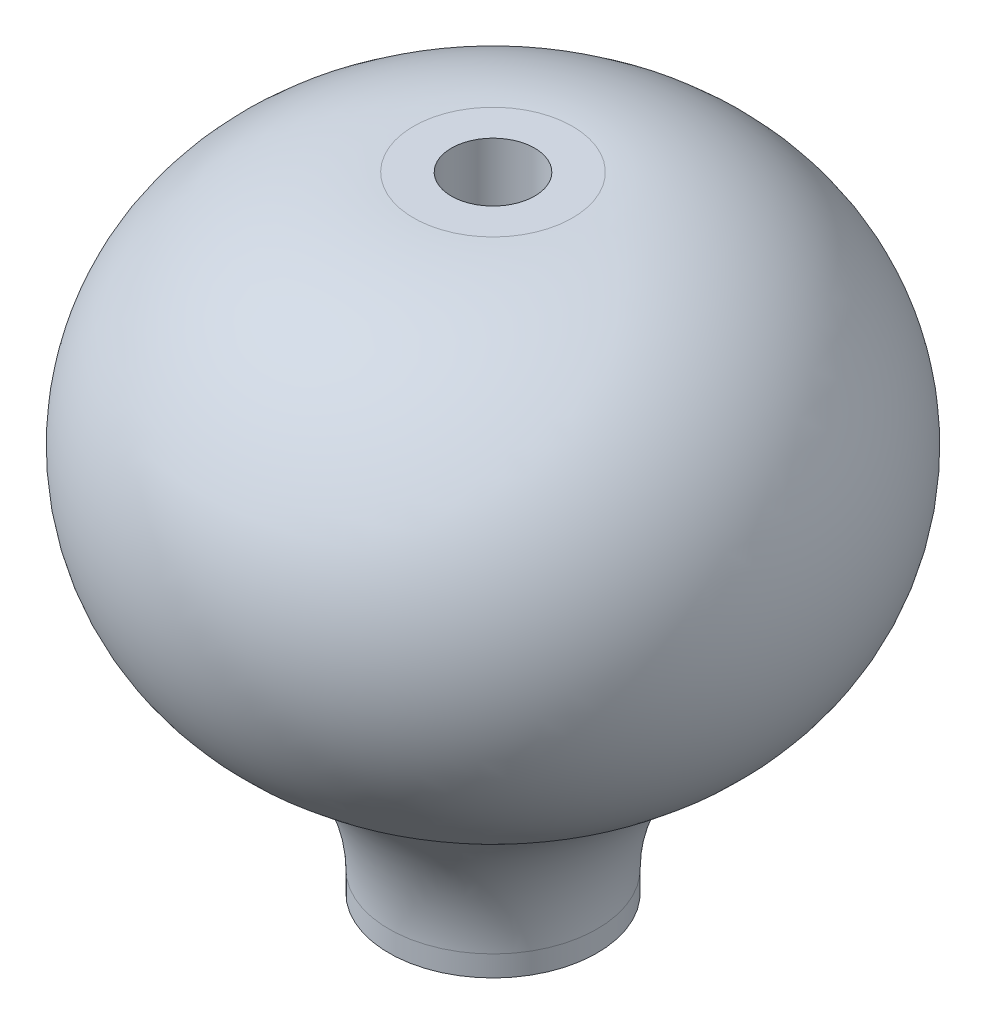
SolidWorks part; units mm, degrees
material "Maple"
ref_plane "Front Plane" through (0, 0, 0) normal (0, 0, 1) x (1, 0, 0)
ref_plane "Top Plane" through (0, 0, 0) normal (0, 1, 0) x (1, 0, 0)
ref_plane "Right Plane" through (0, 0, 0) normal (1, 0, 0) x (0, 0, -1)
sketch "Sketch1" plane through (0, 0, 0) normal (0, 0, 1) x (1, 0, 0)
  line L0 (0, 0) -> (6.35, 0)
  line L3 (0, 0) -> (0, 38.1) construction
  line L4 (17.4376, 1.863) -> (4.8488, 23.6675) construction
  line L5 (0, 0) -> (0, 38.1)
  line L6 (0, 38.1) -> (4.8488, 38.1)
  line L7 (6.35, 0) -> (6.35, 1.27)
  arc A2 (4.8488, 38.1) -> (12.065, 11.1687) centre (4.8488, 23.6675) cw
  arc A3 (6.35, 1.27) -> (12.065, 11.1687) centre (17.78, 1.27) cw
  dimension "D3" = 1.27
  dimension "D5" = 11.43
  dimension "D1" = 6.35
  dimension "D2" = 38.1
  dimension "D4" = 30
revolve "Revolve1" add sketch "Sketch1" angle 360 about L5
sketch "Sketch2" plane through (0, 38.1, 0) normal (0, 1, 0) x (1, 0, 0)
  circle A0 centre (0, 0) radius 2.54
  dimension "D1" = 5.08
extrude "Cut-Extrude1" cut sketch "Sketch2" against normal through all
